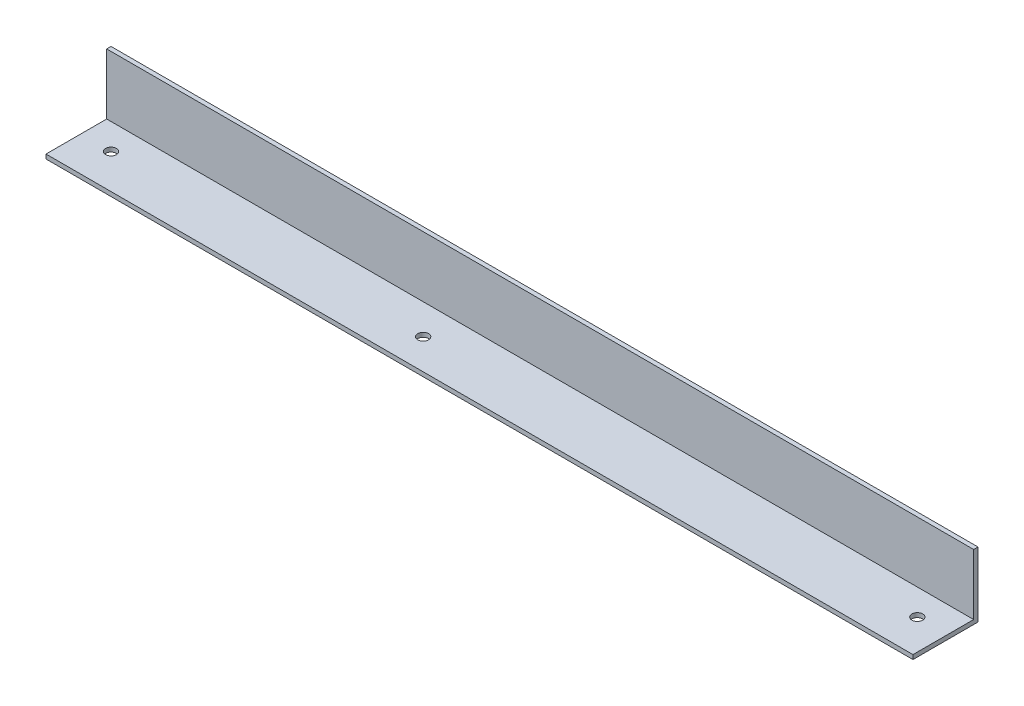
SolidWorks part; units mm, degrees
ref_plane "正面" through (0, 0, 0) normal (0, 0, 1) x (1, 0, 0)
ref_plane "平面" through (0, 0, 0) normal (0, 1, 0) x (1, 0, 0)
ref_plane "右側面" through (0, 0, 0) normal (1, 0, 0) x (0, 0, -1)
sketch "ｽｹｯﾁ1" plane through (0, 0, 0) normal (0, 0, 1) x (1, 0, 0)
  line L1 (0, 0) -> (200, 0)
  line L2 (0, 0) -> (0, 15)
  line L3 (0, 15) -> (200, 15)
  line L4 (200, 0) -> (200, 15)
  dimension "D1" = 200
  dimension "D2" = 15
extrude "ﾎﾞｽ - 押し出し1" add sketch "ｽｹｯﾁ1" along normal blind 1
sketch "ｽｹｯﾁ2" plane through (0, 0, 1) normal (0, 0, 1) x (1, 0, 0)
  line L1 (0, 0) -> (200, 0)
  line L2 (0, 0) -> (0, 1)
  line L3 (0, 1) -> (200, 1)
  line L4 (200, 0) -> (200, 1)
  dimension "D1" = 200
  dimension "D2" = 1
extrude "ﾎﾞｽ - 押し出し2" add sketch "ｽｹｯﾁ2" along normal blind 14
hole_wizard "M3x0.5 ねじ穴1" positions "ｽｹｯﾁ5" profile "ｽｹｯﾁ6" tap size "M3x0.5" standard "JIS" end condition through all
sketch "ｽｹｯﾁ5" plane through (0, 0, 0) normal (0, -1, 0) x (-1, 0, 0)
  line L0 (-200, -15) -> (-200, 0) construction
  line L1 (-8.25, 0) -> (8.25, 0) construction
  point P0 (-193, -7)
  dimension "D1" = 7
  dimension "D2" = 7
sketch "ｽｹｯﾁ6" plane through (193, 0, 7) normal (1, 0, 0) x (0, 0, -1)
  line L0 (0, 0) -> (0, 15)
  line L1 (0, 15) -> (1.25, 15)
  line L2 (1.25, 15) -> (1.25, 0)
  line L5 (1.25, 0) -> (0, 0)
  line L11 (0, -6.35) -> (0, 107.95) construction
  dimension "次ｻｰﾌｪｽまでのねじ下穴ﾄﾞﾘﾙ直径" = 2.5
  dimension "次ｻｰﾌｪｽまでのねじ下穴ﾄﾞﾘﾙの深さ" = 15
cosmetic thread "穴のねじ山3" parameters "D2"=3
hole_wizard "M3x0.5 ねじ穴2" positions "ｽｹｯﾁ7" profile "ｽｹｯﾁ8" tap size "M3x0.5" standard "JIS" end condition through all
sketch "ｽｹｯﾁ7" plane through (0, 1, 0) normal (0, 1, 0) x (1, 0, 0)
  line L0 (200, -15) -> (0, -15) construction
  line L2 (200, -15) -> (200, -1) construction
  point P0 (80, -8)
  dimension "D1" = 7
  dimension "D2" = 120
sketch "ｽｹｯﾁ8" plane through (80, 1, 8) normal (1, 0, 0) x (0, 0, 1)
  line L0 (0, 0) -> (0, 1)
  line L1 (0, 1) -> (1.25, 1)
  line L2 (1.25, 1) -> (1.25, 0)
  line L5 (1.25, 0) -> (0, 0)
  line L11 (0, -6.35) -> (0, 107.95) construction
  dimension "次ｻｰﾌｪｽまでのねじ下穴ﾄﾞﾘﾙ直径" = 2.5
  dimension "次ｻｰﾌｪｽまでのねじ下穴ﾄﾞﾘﾙの深さ" = 1
cosmetic thread "穴のねじ山4" parameters "D2"=3
ref_plane "平面1" through (100, 0, 0) normal (1, 0, 0) x (0, 0, -1)
mirror "ﾐﾗｰ1" about plane through (100, 0, 0) normal (1, 0, 0) of "M3x0.5 ねじ穴1"
